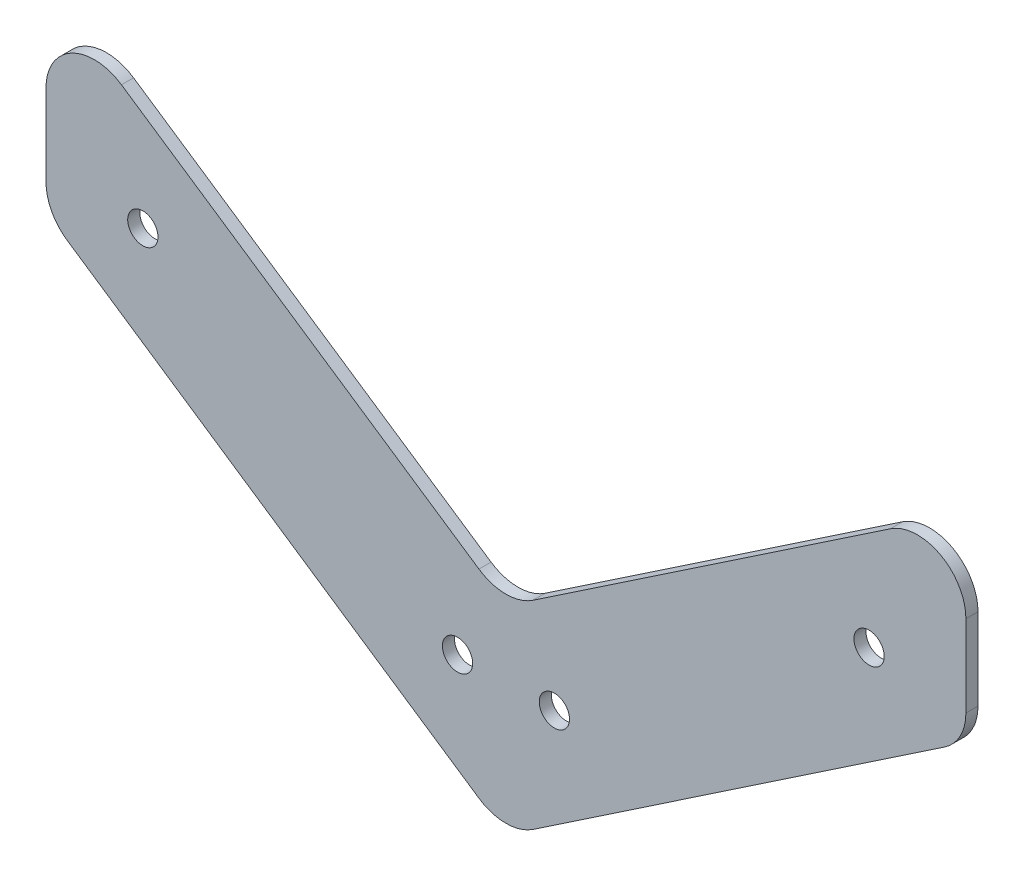
SolidWorks part; units mm, degrees
ref_plane "Front Plane" through (0, 0, 0) normal (0, 0, 1) x (1, 0, 0)
ref_plane "Top Plane" through (0, 0, 0) normal (0, 1, 0) x (1, 0, 0)
ref_plane "Right Plane" through (0, 0, 0) normal (1, 0, 0) x (0, 0, -1)
sketch "Sketch1" plane through (0, 0, 0) normal (0, 0, 1) x (1, 0, 0)
  line L0 (0, -52.0541) -> (0, 0) construction
  line L1 (0, 0) -> (-120.65, 81.2276)
  line L2 (0, 0) -> (120.65, 81.2276)
  line L3 (120.65, 81.2276) -> (120.65, 29.1735)
  line L4 (120.65, 29.1735) -> (0, -52.0541)
  line L5 (0, -52.0541) -> (-120.65, 29.1735)
  line L6 (-120.65, 29.1735) -> (-120.65, 81.2276)
  line L7 (0, -26.0271) -> (-120.65, 55.2005) construction
  line L8 (0, -26.0271) -> (120.65, 55.2005) construction
  circle A0 centre (-95.25, 38.1) radius 3.9687
  circle A1 centre (95.25, 38.1) radius 3.9687
  circle A2 centre (-12.7, -17.4768) radius 3.9688
  circle A3 centre (12.7, -17.4768) radius 3.9688
  point P3 (0, -26.0271)
  point P12 (-120.65, 55.2005)
  point P15 (120.65, 55.2005)
  dimension "D2" = 7.9375
  dimension "D1" = 241.3
  dimension "D3" = 21.59
  dimension "D4" = 95.25
  dimension "D5" = 95.25
  dimension "D6" = 38.1
  dimension "D8" = 25.4
extrude "Boss-Extrude1" add sketch "Sketch1" along normal blind 3.175
fillet "Fillet1" radius 12.7 6 edges at (0, -52.0541, 1.5875) (0, 0, 1.5875) (120.65, 29.1735, 1.5875) (120.65, 81.2276, 1.5875) (-120.65, 29.1735, 1.5875) (-120.65, 81.2276, 1.5875)
